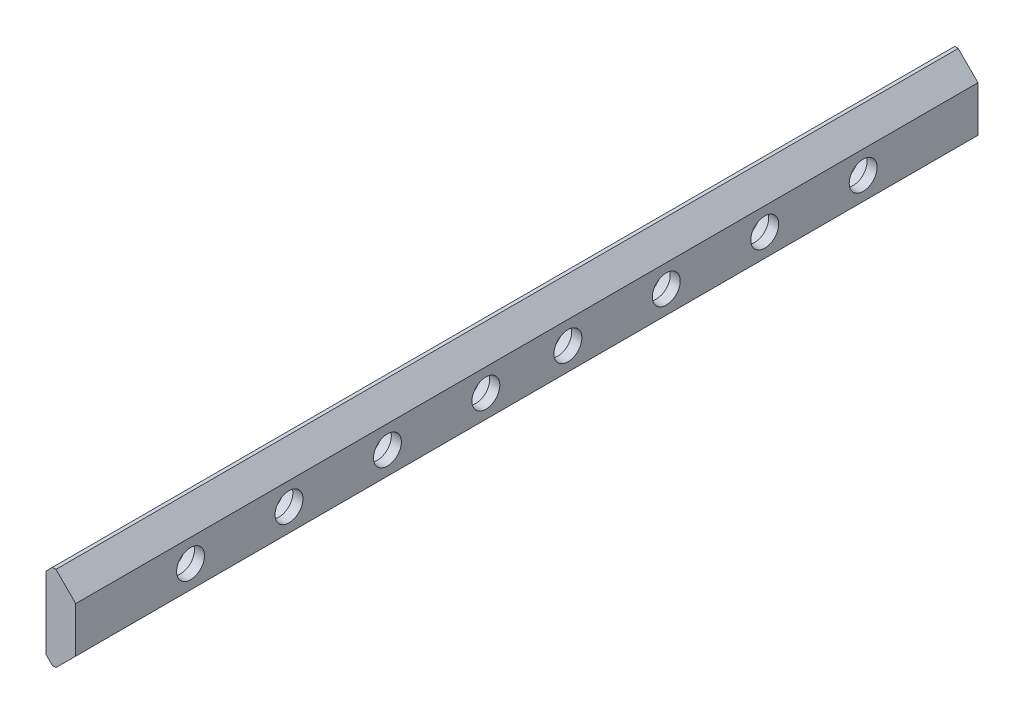
SolidWorks part; units mm, degrees
ref_plane "Front Plane" through (0, 0, 0) normal (0, 0, 1) x (1, 0, 0)
ref_plane "Top Plane" through (0, 0, 0) normal (0, 1, 0) x (1, 0, 0)
ref_plane "Right Plane" through (0, 0, 0) normal (1, 0, 0) x (0, 0, -1)
sketch "Sketch1" plane through (0, 0, 0) normal (0, 0, 1) x (1, 0, 0)
  line L1 (-1.8125, 5.4) -> (-0.8125, 5.4)
  line L2 (-0.8125, 5.4) -> (1.8125, 2.775)
  line L3 (1.8125, 2.775) -> (1.8125, -2.775)
  line L4 (1.8125, -2.775) -> (-0.8125, -5.4)
  line L5 (-0.8125, -5.4) -> (-1.8125, -5.4)
  line L7 (1.8125, 2.775) -> (-1.8125, 2.775) construction
  line L8 (-1.8125, 5.4) -> (-1.8125, -5.4)
  point P0 (1.8125, 0)
  point P2 (-1.8125, 0)
  point P3 (0, 2.775)
  dimension "D1" = 10.8
  dimension "D2" = 5.55
  dimension "D3" = 1
extrude "Boss-Extrude2" add sketch "Sketch1" along normal blind 110
hole_wizard "Chambrage pour vis à tête ronde bombée M2.51" positions "Esquisse1" profile "Esquisse2" counterbore size "M2.5" standard "Ansi Metric"
sketch "Esquisse1" plane through (-1.8125, 0, 0) normal (1, 0, 0) x (0, 0, -1)
  line L0 (-101, 0) -> (-89, 0) construction
  line L1 (-89, 0) -> (-77, 0) construction
  line L2 (-77, 0) -> (-65, 0) construction
  line L4 (-45, 0) -> (-33, 0) construction
  line L5 (-33, 0) -> (-21, 0) construction
  line L6 (-21, 0) -> (-9, 0) construction
  line L11 (-45, 0) -> (-65, 0) construction
  line L13 (-55, 0) -> (-55, 5.4) construction
  line L15 (-110, 5.4) -> (0, 5.4) construction
  point P0 (-101, 0)
  point P3 (-89, 0)
  point P6 (-77, 0)
  point P9 (-65, 0)
  point P12 (-45, 0)
  point P15 (-21, 0)
  point P18 (-9, 0)
  point P21 (-33, 0)
  dimension "D1" = 20
  dimension "D2" = 12
  dimension "D3" = 5.4
sketch "Esquisse2" plane through (-1.8125, 0, 96) normal (0, 1, 0) x (0, 0, 1)
  line L0 (0, 0) -> (0, 3.625)
  line L1 (0, 3.625) -> (1.45, 3.625)
  line L3 (1.45, 3.625) -> (1.45, 2.625)
  line L4 (1.45, 2.625) -> (3, 2.625)
  line L5 (3, 2.625) -> (3, 0)
  line L7 (3, 0) -> (0, 0)
  line L11 (0, -6.35) -> (0, 107.95) construction
  dimension "Diamètre du perçage jusqu'au prochain" = 2.9
  dimension "Profondeur du perçage jusqu'au prochain" = 3.625
  dimension "Diamètre du chambrage" = 6
  dimension "Profondeur du chambrage" = 2.625
hole_wizard "Chambrage pour vis à tête ronde bombée M31" positions "Esquisse3" profile "Esquisse4" counterbore size "M3" standard "Ansi Metric"
sketch "Esquisse3" plane through (-1.8125, 0, 0) normal (-1, 0, 0) x (0, 0, 1)
  point P0 (9, 0)
  point P3 (21, 0)
  point P6 (33, 0)
  point P9 (45, 0)
  point P12 (65, 0)
  point P15 (77, 0)
  point P18 (89, 0)
  point P21 (101, 0)
sketch "Esquisse4" plane through (-1.8125, 0, 9) normal (0, 1, 0) x (0, 0, 1)
  line L0 (0, 0) -> (0, 3.625)
  line L1 (0, 3.625) -> (1.7, 3.625)
  line L3 (1.7, 3.625) -> (1.7, 2.4)
  line L4 (1.7, 2.4) -> (3.5, 2.4)
  line L5 (3.5, 2.4) -> (3.5, 0)
  line L7 (3.5, 0) -> (0, 0)
  line L11 (0, -6.35) -> (0, 107.95) construction
  dimension "Diamètre du perçage jusqu'au prochain" = 3.4
  dimension "Profondeur du perçage jusqu'au prochain" = 3.625
  dimension "Diamètre du chambrage" = 7
  dimension "Profondeur du chambrage" = 2.4
hole_wizard "Chambrage pour vis à tête ronde bombée M32" positions "Esquisse5" profile "Esquisse6" counterbore size "M3" standard "Ansi Metric"
sketch "Esquisse5" plane through (-1.8125, 0, 0) normal (-1, 0, 0) x (0, 0, 1)
  line L0 (55, 5.4) -> (55, -5.4) construction
  line L1 (110, 5.4) -> (0, 5.4) construction
  line L2 (110, -5.4) -> (0, -5.4) construction
  line L4 (55, 0) -> (50, 0) construction
  line L5 (50, 0) -> (38, 0) construction
  point P9 (50, 0)
  point P18 (38, 0)
  point P19 (26, 0)
  point P20 (14, 0)
  point P23 (72, 0)
  point P24 (84, 0)
  point P25 (96, 0)
  point P26 (60, 0)
  dimension "D1" = 5
  dimension "D3" = 12
  dimension "D2" = 4
sketch "Esquisse6" plane through (-1.8125, 0, 60) normal (0, 1, 0) x (0, 0, 1)
  line L0 (0, 0) -> (0, 7)
  line L1 (0, 7) -> (1.7, 7)
  line L2 (1.7, 7) -> (1.7, 2.4)
  line L3 (1.7, 2.4) -> (3.5, 2.4)
  line L4 (3.5, 2.4) -> (3.5, 0)
  line L5 (3.5, 0) -> (0, 0)
  line L10 (0, 7) -> (-1.7, 7) construction
  line L11 (0, -6.35) -> (0, 107.95) construction
  dimension "Diamètre du perçage" = 3.4
  dimension "Profondeur du perçage" = 7
  dimension "Diamètre du chambrage" = 7
  dimension "Profondeur du chambrage" = 2.4
  dimension "Angle de pointe" = 180
sketch "Sketch2" plane through (0, 0, 110) normal (0, 0, 1) x (1, 0, 0)
  line L0 (-0.8125, 5.4) -> (-1.8125, 4.4)
  line L1 (-1.8125, 5.4) -> (-1.8125, -5.4) construction
  line L2 (-1.8125, 4.4) -> (-1.8125, 5.4)
  line L3 (-1.8125, 5.4) -> (-0.8125, 5.4)
  line L4 (-0.8125, -5.4) -> (-1.8125, -4.4)
  line L5 (-1.8125, -4.4) -> (-1.8125, -5.4)
  line L6 (-1.8125, -5.4) -> (-0.8125, -5.4)
  dimension "D1" = 45
  dimension "D2" = 45
extrude "Cut-Extrude1" cut sketch "Sketch2" against normal through all
chamfer "Chamfer1" distance 0.3 angle 45 2 edges at (-0.8125, 5.4, 55) (-0.8125, -5.4, 55)
